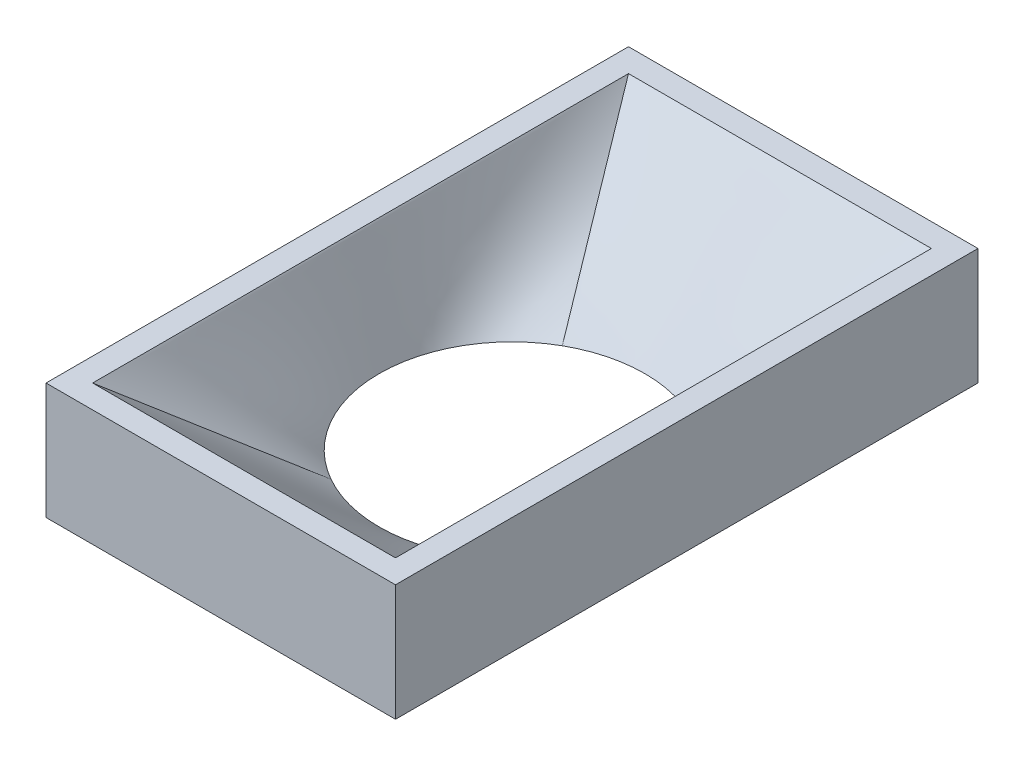
SolidWorks part; units mm, degrees
ref_plane "Front" through (0, 0, 0) normal (0, 0, 1) x (1, 0, 0)
ref_plane "Top" through (0, 0, 0) normal (0, 1, 0) x (1, 0, 0)
ref_plane "Right" through (0, 0, 0) normal (1, 0, 0) x (0, 0, -1)
sketch "Sketch1" plane through (0, 0, 0) normal (0, 1, 0) x (1, 0, 0)
  line L1 (-19.05, 31.75) -> (19.05, 31.75)
  line L2 (-19.05, 31.75) -> (-19.05, -31.75)
  line L3 (-19.05, -31.75) -> (19.05, -31.75)
  line L4 (19.05, 31.75) -> (19.05, -31.75)
  line L5 (-19.05, 31.75) -> (19.05, -31.75) construction
  line L6 (-19.05, -31.75) -> (19.05, 31.75) construction
  point P0 (0, 0)
  dimension "D1" = 38.1
  dimension "D2" = 63.5
extrude "Boss-Extrude1" add sketch "Sketch1" along normal blind 12.7
sketch "Sketch2" plane through (0, 0, 0) normal (0, -1, 0) x (1, 0, 0)
  circle A0 centre (0, 0) radius 14.478
  dimension "D1" = 28.956
sketch "Sketch4" plane through (0, 12.7, 0) normal (0, 1, 0) x (1, 0, 0)
  line L14 (-16.51, -29.21) -> (16.51, -29.21)
  line L15 (16.51, -29.21) -> (16.51, 29.21)
  line L16 (-16.51, 29.21) -> (-16.51, -29.21)
  line L17 (16.51, 29.21) -> (-16.51, 29.21)
  line L18 (-16.51, -29.21) -> (16.51, -29.21)
  line L19 (16.51, -29.21) -> (16.51, 29.21)
  line L20 (-16.51, 29.21) -> (-16.51, -29.21)
  line L21 (16.51, 29.21) -> (-16.51, 29.21)
  dimension "D1" = 2.54
loft "Cut-Loft1" cut profiles "Sketch2", "Sketch4"
